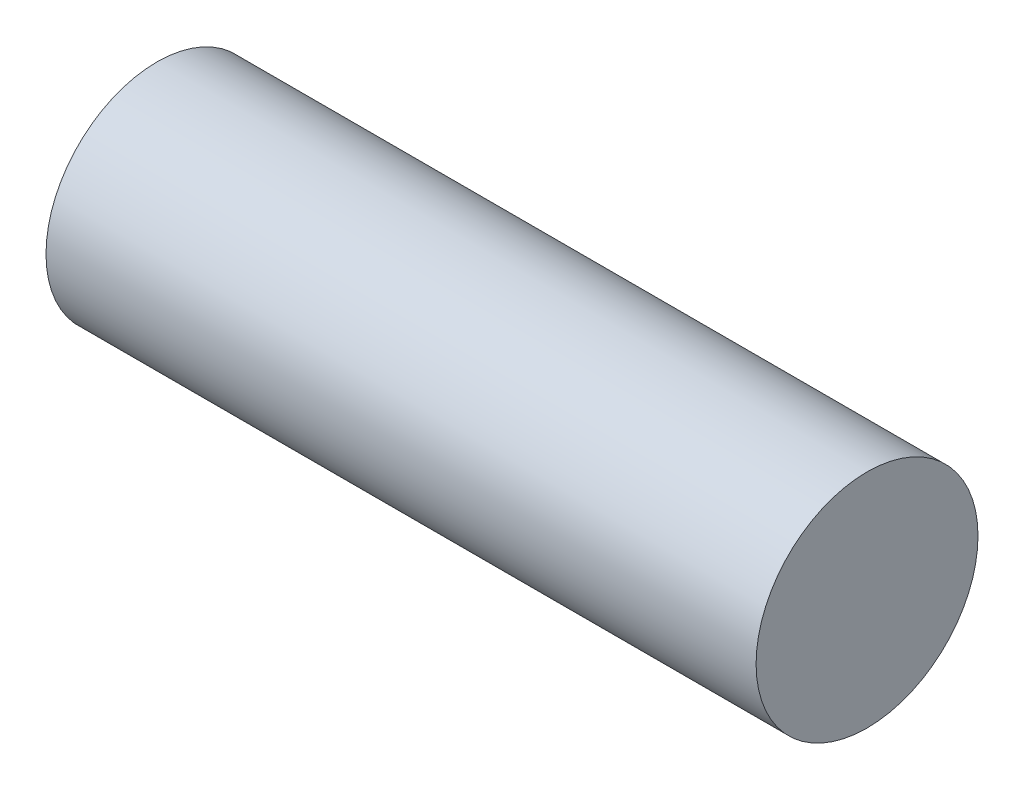
SolidWorks part; units mm, degrees
ref_plane "Front Plane" through (0, 0, 0) normal (0, 0, 1) x (1, 0, 0)
ref_plane "Top Plane" through (0, 0, 0) normal (0, 1, 0) x (1, 0, 0)
ref_plane "Right Plane" through (0, 0, 0) normal (1, 0, 0) x (0, 0, -1)
sketch "Sketch1" plane through (0, 0, 0) normal (1, 0, 0) x (0, 0, -1)
  circle A0 centre (0, 0) radius 2.5
  dimension "D1" = 5
extrude "Boss-Extrude1" add sketch "Sketch1" along normal blind 16
